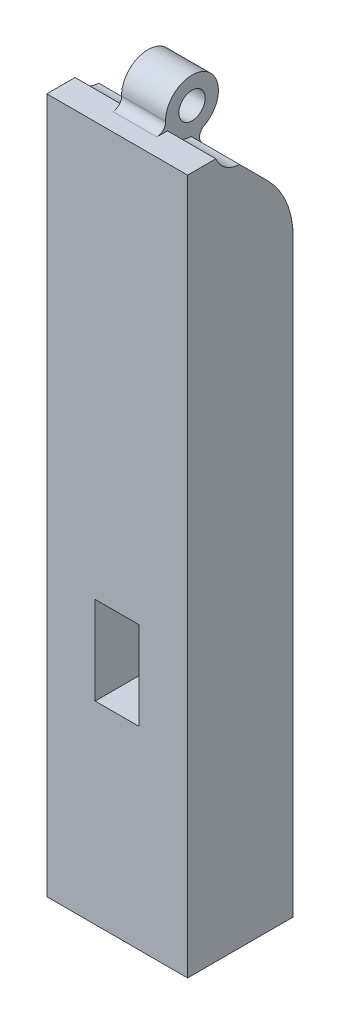
SolidWorks part; units mm, degrees
ref_plane "Front Plane" through (0, 0, 0) normal (0, 0, 1) x (1, 0, 0)
ref_plane "Top Plane" through (0, 0, 0) normal (0, 1, 0) x (1, 0, 0)
ref_plane "Right Plane" through (0, 0, 0) normal (1, 0, 0) x (0, 0, -1)
sketch "Sketch1" plane through (0, 0, 0) normal (0, 0, 1) x (1, 0, 0)
  line L0 (-8, 0) -> (8, 0)
  line L1 (8, 0) -> (8, -79)
  line L2 (8, -79) -> (-8, -79)
  line L3 (-8, -79) -> (-8, 0)
  point P4 (0, 0)
extrude "Boss-Extrude1" add sketch "Sketch1" along normal blind 12
sketch "Sketch2" plane through (0, 0, 0) normal (1, 0, 0) x (0, 0, -1)
  line L0 (-12, 0) -> (-8, 0)
  line L1 (-12, 0) -> (0, 0) construction
  line L2 (0, -79) -> (0, 0) construction
  line L3 (-8, 0) -> (0, 0)
  line L6 (0, 0) -> (0, -8)
  line L7 (-8, 0) -> (0, -8)
extrude "Cut-Extrude1" cut sketch "Sketch2" against normal through all both and the other way through all contours L3 L6 L7
sketch "Sketch3" plane through (0, 0, 0) normal (1, 0, 0) x (0, 0, -1)
  line L0 (-12, 0) -> (0, 0)
  line L1 (-6, 0) -> (-6, 1.1)
  circle A0 centre (-6, 1.1) radius 1.5
  circle A1 centre (-6, 1.1) radius 3
extrude "Cut-Extrude2" cut sketch "Sketch3" against normal through all both and the other way through all contours L0 A1 A0 | L0 A1 A0
sketch "Sketch4" plane through (0, 0, 0) normal (1, 0, 0) x (0, 0, -1)
  circle A0 centre (-6, 1.1) radius 1.5
  circle A1 centre (-6, 1.1) radius 3
extrude "Boss-Extrude2" add sketch "Sketch4" along normal mid plane 5
fillet "Fillet1" radius 1 2 edges at (0, 0, 8.7911) (0, -1.8983, 6.1017)
fillet "Fillet2" radius 10 1 edges at (0, -8, 0)
sketch "Sketch5" plane through (0, 0, 0) normal (0, 0, -1) x (-1, 0, 0)
  line L2 (-2.5, -47) -> (2.5, -47)
  line L3 (-2.5, -37) -> (2.5, -37)
  line L4 (-2.5, -37) -> (-2.5, -47)
  line L5 (-2.5, -47) -> (2.5, -47)
  line L6 (2.5, -37) -> (2.5, -47)
  line L7 (-2.5, -37) -> (2.5, -47) construction
  line L8 (-2.5, -47) -> (2.5, -37) construction
  line L9 (-2.5, -47) -> (-2.5, -57)
  line L10 (-2.5, -57) -> (2.5, -57)
  line L11 (2.5, -47) -> (2.5, -57)
  line L12 (-2.5, -37) -> (2.5, -37)
  line L13 (-2.5, -37) -> (-2.5, -27)
  line L14 (-2.5, -27) -> (2.5, -27)
  line L15 (2.5, -37) -> (2.5, -27)
extrude "Cut-Extrude3" cut sketch "Sketch5" against normal blind 5 contours L3 L15 L14 L13 | L11 L2 L9 L10
sketch "Sketch6" plane through (0, -47, 0) normal (0, -1, 0) x (1, 0, 0)
  line L0 (2.5, 5) -> (2.5, 0) construction
  line L1 (-2.5, 5) -> (2.5, 5)
  line L2 (-2.5, 5) -> (-2.5, 2.5)
  line L3 (-2.5, 2.5) -> (2.5, 2.5)
  line L4 (2.5, 5) -> (2.5, 2.5)
extrude "Cut-Extrude4" cut sketch "Sketch6" against normal up to next
sketch "Sketch7" plane through (0, 0, 0) normal (0, 0, -1) x (-1, 0, 0)
  line L1 (-2.5, -47) -> (2.5, -47)
  line L2 (-2.5, -47) -> (-2.5, -57)
  line L3 (-2.5, -57) -> (2.5, -57)
  line L4 (2.5, -47) -> (2.5, -57)
extrude "Cut-Extrude5" cut sketch "Sketch7" against normal through all
